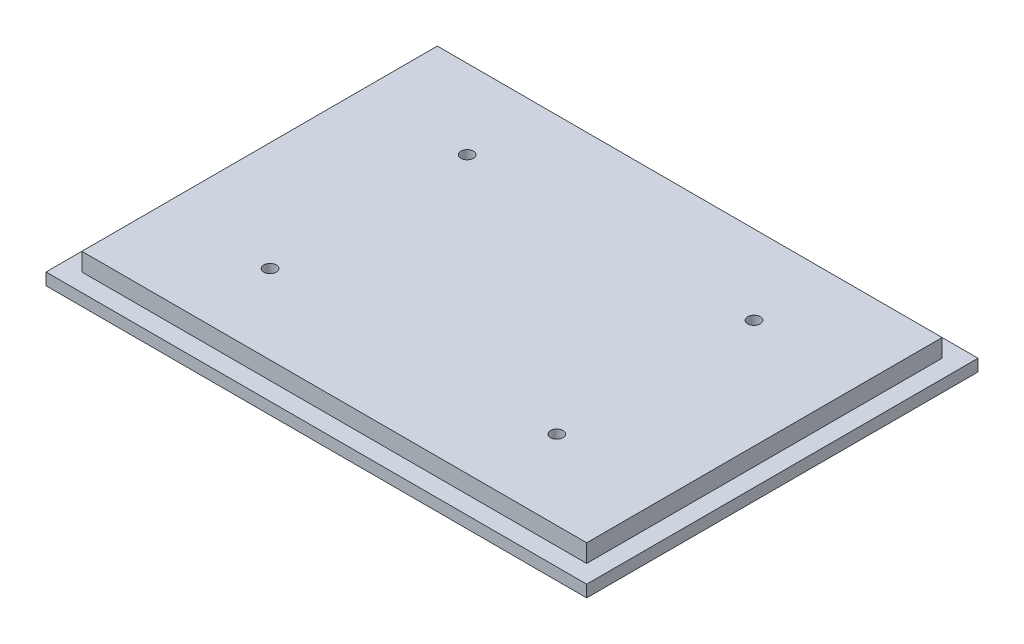
SolidWorks part; units mm, degrees
ref_plane "Plan de face" through (0, 0, 0) normal (0, 0, 1) x (1, 0, 0)
ref_plane "Plan de dessus" through (0, 0, 0) normal (0, 1, 0) x (1, 0, 0)
ref_plane "Plan de droite" through (0, 0, 0) normal (1, 0, 0) x (0, 0, -1)
sketch "Esquisse1" plane through (0, 0, 0) normal (0, 1, 0) x (1, 0, 0)
  line L1 (-84.5, -59.5) -> (84.5, -59.5)
  line L2 (-84.5, -59.5) -> (-84.5, 59.5)
  line L3 (-84.5, 59.5) -> (84.5, 59.5)
  line L4 (84.5, -59.5) -> (84.5, 59.5)
  line L5 (-84.5, -59.5) -> (84.5, 59.5) construction
  line L6 (-84.5, 59.5) -> (84.5, -59.5) construction
  point P0 (0, 0)
  dimension "D1" = 169
  dimension "D2" = 119
extrude "Boss.-Extru.1" add sketch "Esquisse1" along normal blind 10
sketch "Esquisse2" plane through (0, 0, 0) normal (0, 1, 0) x (1, 0, 0)
  line L0 (-84.5, 59.5) -> (-84.5, -59.5) construction
  line L1 (-90.5, -65.5) -> (90.5, -65.5)
  line L2 (-90.5, -65.5) -> (-90.5, 65.5)
  line L3 (-90.5, 65.5) -> (90.5, 65.5)
  line L4 (90.5, -65.5) -> (90.5, 65.5)
  line L5 (-90.5, -65.5) -> (90.5, 65.5) construction
  line L6 (-90.5, 65.5) -> (90.5, -65.5) construction
  line L7 (84.5, 59.5) -> (-84.5, 59.5) construction
  point P0 (0, 0)
  dimension "D1" = 6
  dimension "D2" = 6
extrude "Boss.-Extru.2" add sketch "Esquisse2" along normal blind 4
sketch "Esquisse3" plane through (0, 10, 0) normal (0, 1, 0) x (1, 0, 0)
  line L0 (-48, 33) -> (48, -33) construction
  line L1 (48, 33) -> (-48, -33) construction
  circle A0 centre (-48, 33) radius 2.1
  circle A1 centre (48, 33) radius 2.1
  circle A2 centre (48, -33) radius 2.1
  circle A3 centre (-48, -33) radius 2.1
  point P8 (0, 0)
  dimension "D3" = 4.2
  dimension "D1" = 66
  dimension "D2" = 96
extrude "Enlèv. mat.-Extru.1" cut sketch "Esquisse3" against normal through all
